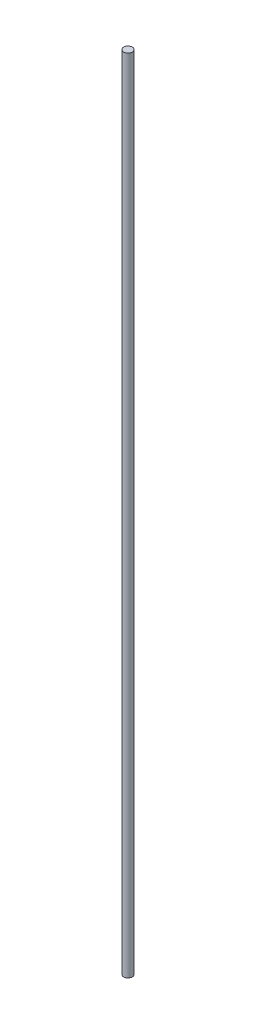
SolidWorks part; units mm, degrees
ref_plane "Front Plane" through (0, 0, 0) normal (0, 0, 1) x (1, 0, 0)
ref_plane "Top Plane" through (0, 0, 0) normal (0, 1, 0) x (1, 0, 0)
ref_plane "Right Plane" through (0, 0, 0) normal (1, 0, 0) x (0, 0, -1)
sketch "Sketch1" plane through (0, 0, 0) normal (0, 1, 0) x (1, 0, 0)
  circle A0 centre (0, 0) radius 4
  dimension "D1" = 8
extrude "Boss-Extrude1" add sketch "Sketch1" along normal blind 740
